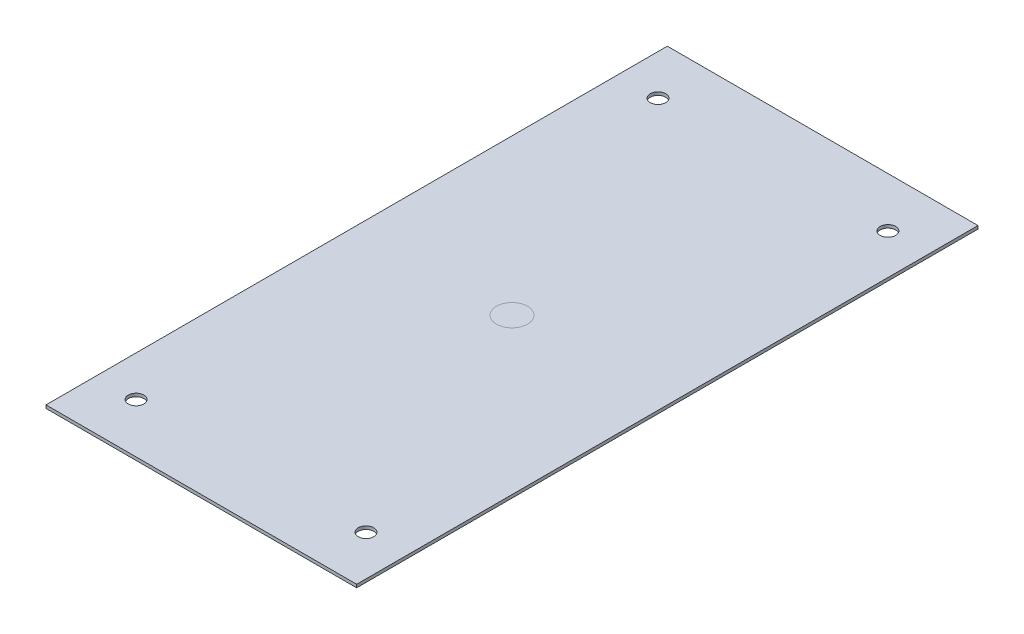
SolidWorks part; units mm, degrees
material "STD Carbon Fibre"
ref_plane "Front Plane" through (0, 0, 0) normal (0, 0, 1) x (1, 0, 0)
ref_plane "Top Plane" through (0, 0, 0) normal (0, 1, 0) x (1, 0, 0)
ref_plane "Right Plane" through (0, 0, 0) normal (1, 0, 0) x (0, 0, -1)
sketch "Sketch1" plane through (0, 0, 0) normal (0, 1, 0) x (1, 0, 0)
  line L1 (50, -100) -> (-50, -100)
  line L2 (50, -100) -> (50, 100)
  line L3 (50, 100) -> (-50, 100)
  line L4 (-50, -100) -> (-50, 100)
  line L5 (50, -100) -> (-50, 100) construction
  line L6 (50, 100) -> (-50, -100) construction
  point P0 (0, 0)
  dimension "D1" = 100
  dimension "D2" = 200
extrude "Boss-Extrude1" add sketch "Sketch1" along normal blind 1
sketch "Sketch3" plane through (0, 1, 0) normal (0, 1, 0) x (1, 0, 0)
  circle A0 centre (37, 84) radius 2.5 construction
  circle A1 centre (37, 84) radius 2.5
extrude "Cut-Extrude1" cut sketch "Sketch3" against normal through all
mirror "Mirror1" about plane through (0, 0, 0) normal (1, 0, 0) of "Cut-Extrude1"
mirror "Mirror2" about plane through (0, 0, 0) normal (0, 0, 1) of "Cut-Extrude1", "Mirror1"
sketch "Sketch4" plane through (0, 1, 0) normal (0, 1, 0) x (1, 0, 0)
  circle A0 centre (0, 0) radius 5
  dimension "D1" = 10
split line "Split Line1"
